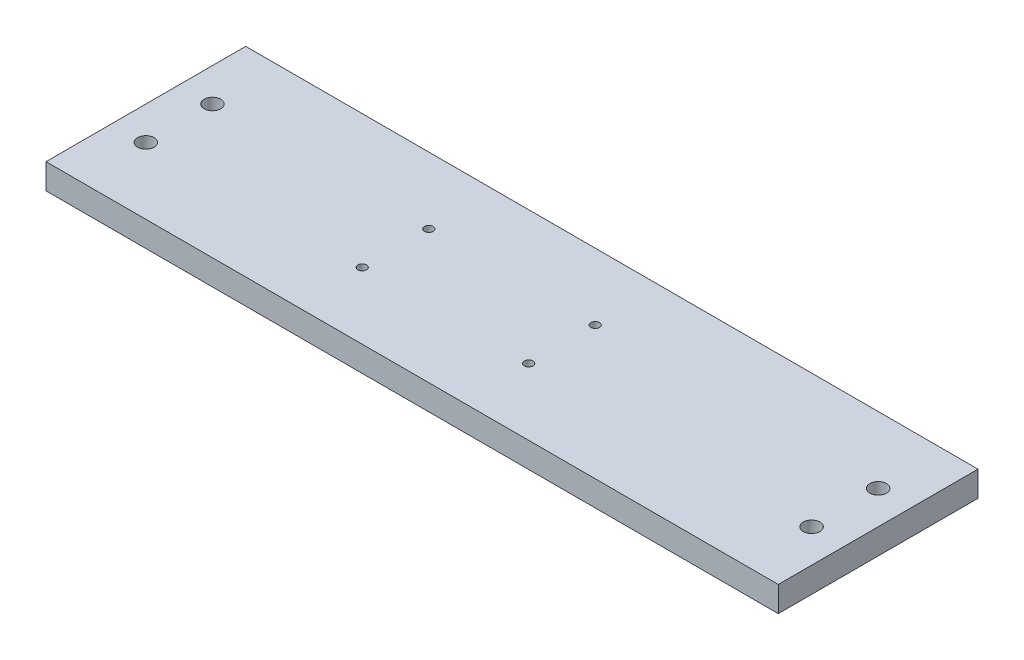
SolidWorks part; units mm, degrees
ref_plane "Front Plane" through (0, 0, 0) normal (0, 0, 1) x (1, 0, 0)
ref_plane "Top Plane" through (0, 0, 0) normal (0, 1, 0) x (1, 0, 0)
ref_plane "Right Plane" through (0, 0, 0) normal (1, 0, 0) x (0, 0, -1)
sketch "Sketch1" plane through (0, 0, 0) normal (0, 1, 0) x (1, 0, 0)
  line L0 (-55, 0) -> (55, 0) construction
  line L1 (139.7, 38.1) -> (-139.7, 38.1)
  line L2 (139.7, 38.1) -> (139.7, -38.1)
  line L3 (139.7, -38.1) -> (-139.7, -38.1)
  line L4 (-139.7, 38.1) -> (-139.7, -38.1)
  line L5 (139.7, 38.1) -> (-139.7, -38.1) construction
  line L6 (139.7, -38.1) -> (-139.7, 38.1) construction
  circle A0 centre (127, 12.7) radius 3.175
  circle A1 centre (19.05, 12.7) radius 1.651
  circle A2 centre (-44.45, 12.7) radius 1.651
  circle A3 centre (-127, 12.7) radius 3.175
  circle A4 centre (127, -12.7) radius 3.175
  circle A5 centre (19.05, -12.7) radius 1.651
  circle A6 centre (-44.45, -12.7) radius 1.651
  circle A7 centre (-127, -12.7) radius 3.175
  point P0 (0, 0)
  dimension "D7" = 6.35
  dimension "D8" = 3.302
  dimension "D1" = 279.4
  dimension "D2" = 76.2
  dimension "D3" = 107.95
  dimension "D4" = 12.7
  dimension "D5" = 82.55
  dimension "D6" = 63.5
  dimension "D9" = 25.4
extrude "Boss-Extrude1" add sketch "Sketch1" along normal mid plane 9.652
